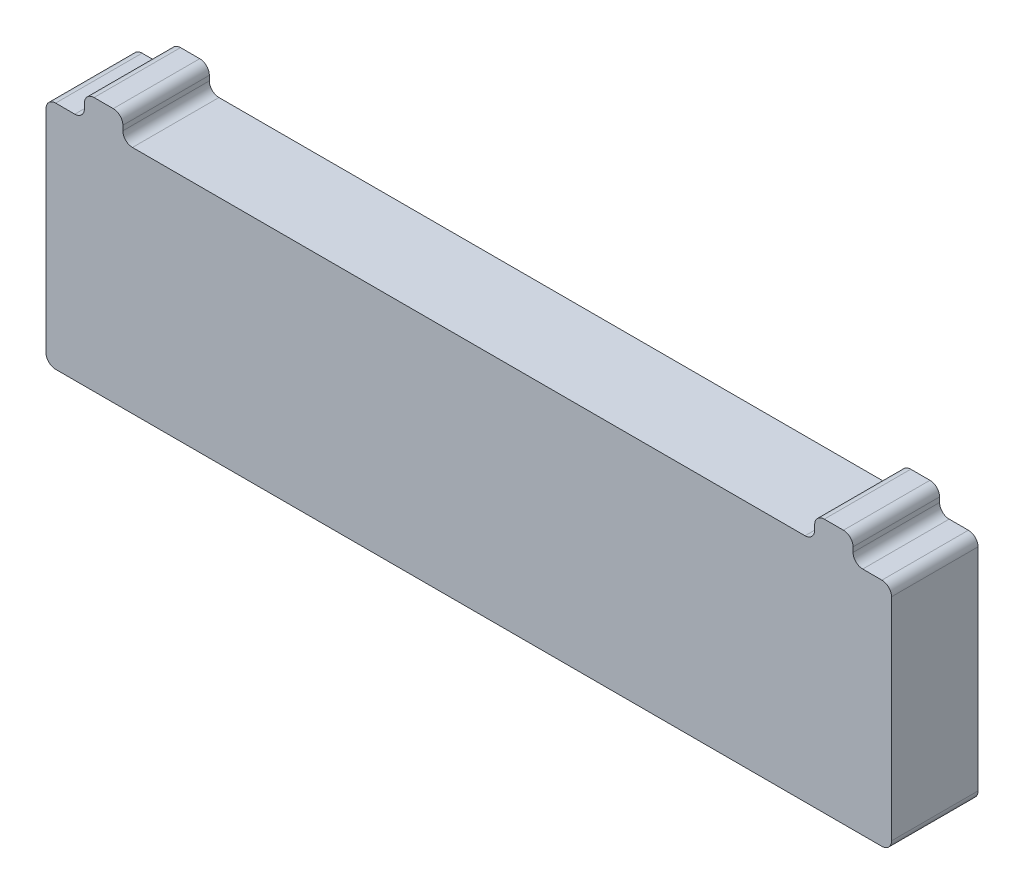
SolidWorks part; units mm, degrees
material "ABS"
ref_plane "Front" through (0, 0, 0) normal (0, 0, 1) x (1, 0, 0)
ref_plane "Top" through (0, 0, 0) normal (0, 1, 0) x (1, 0, 0)
ref_plane "Right" through (0, 0, 0) normal (1, 0, 0) x (0, 0, -1)
sketch "Esquisse1" plane through (0, 0, 0) normal (0, 0, 1) x (1, 0, 0)
  line L1 (-44, -24) -> (44, -24)
  line L2 (-44, -24) -> (-44, 0)
  line L3 (-44, 0) -> (44, 0)
  line L4 (44, -24) -> (44, 0)
  dimension "D1" = 88
  dimension "D2" = 24
extrude "Boss.-Extru.1" add sketch "Esquisse1" along normal blind 9
sketch "Esquisse2" plane through (0, 0, 9) normal (0, 0, 1) x (1, 0, 0)
  line L0 (44, 0) -> (-44, 0) construction
  line L1 (-36, 0) -> (-40, 0)
  line L2 (-36, 0) -> (-36, 2.5)
  line L3 (-36, 2.5) -> (-40, 2.5)
  line L4 (-40, 0) -> (-40, 2.5)
  line L5 (0, -50) -> (0, 50) construction
  line L6 (40, 0) -> (40, 2.5)
  line L7 (36, 2.5) -> (40, 2.5)
  line L8 (36, 0) -> (36, 2.5)
  line L9 (36, 0) -> (40, 0)
  dimension "D1" = 76
  dimension "D2" = 4
  dimension "D3" = 2.5
extrude "Boss.-Extru.2" add sketch "Esquisse2" against normal up to surface (9 mm away) up to face at (0, -12, 0)
fillet "Congé1" radius 1 12 edges at (-40, 0, 4.5) (-40, 2.5, 4.5) (-36, 2.5, 4.5) (-36, 0, 4.5) (36, 0, 4.5) (36, 2.5, 4.5) (40, 2.5, 4.5) (40, 0, 4.5) (44, 0, 4.5) (44, -24, 4.5) (-44, -24, 4.5) (-44, 0, 4.5)
